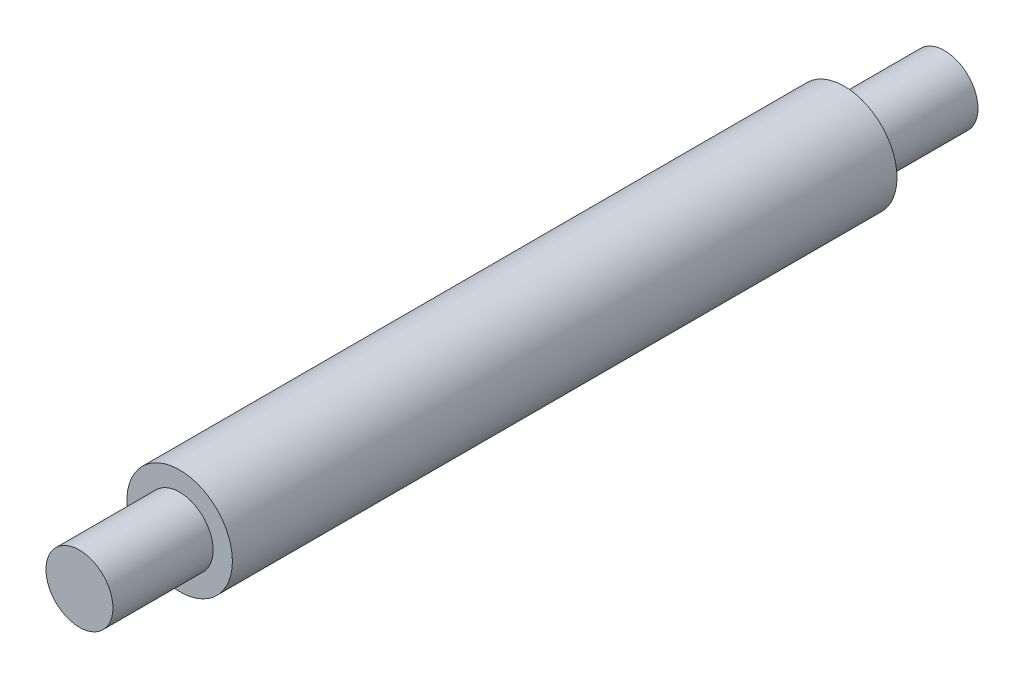
SolidWorks part; units mm, degrees
ref_plane "Front Plane" through (0, 0, 0) normal (0, 0, 1) x (1, 0, 0)
ref_plane "Top Plane" through (0, 0, 0) normal (0, 1, 0) x (1, 0, 0)
ref_plane "Right Plane" through (0, 0, 0) normal (1, 0, 0) x (0, 0, -1)
sketch "Sketch1" plane through (0, 0, 0) normal (0, 0, 1) x (1, 0, 0)
  circle A0 centre (0, 0) radius 3.175
  dimension "D1" = 6.35
extrude "Boss-Extrude1" add sketch "Sketch1" along normal mid plane 82
sketch "Sketch2" plane through (0, 0, 0) normal (0, 0, 1) x (1, 0, 0)
  circle A0 centre (0, 0) radius 5
  dimension "D1" = 10
extrude "Boss-Extrude2" add sketch "Sketch2" along normal mid plane 63 separate body
